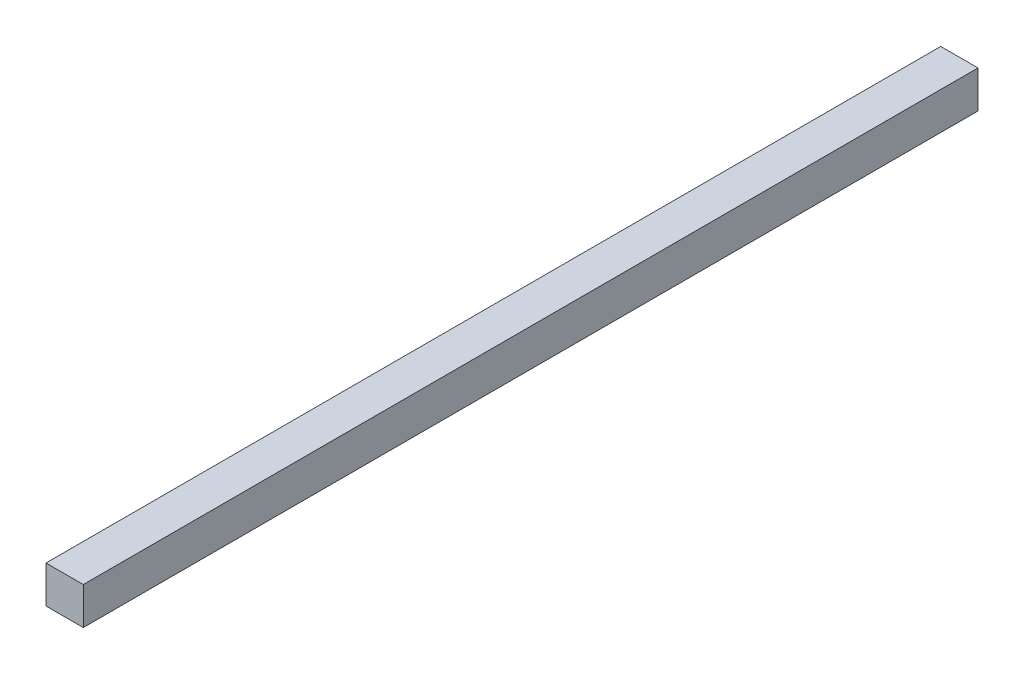
SolidWorks part; units mm, degrees
ref_plane "Front Plane" through (0, 0, 0) normal (0, 0, 1) x (1, 0, 0)
ref_plane "Top Plane" through (0, 0, 0) normal (0, 1, 0) x (1, 0, 0)
ref_plane "Right Plane" through (0, 0, 0) normal (1, 0, 0) x (0, 0, -1)
sketch "Sketch2" plane through (0, 0, 0) normal (0, 0, 1) x (1, 0, 0)
  line L1 (0, 0) -> (6.35, 0)
  line L2 (0, 0) -> (0, 6.35)
  line L3 (0, 6.35) -> (6.35, 6.35)
  line L4 (6.35, 0) -> (6.35, 6.35)
  dimension "D1" = 6.35
  dimension "D2" = 6.35
extrude "Boss-Extrude1" add sketch "Sketch2" along normal blind 152.4
